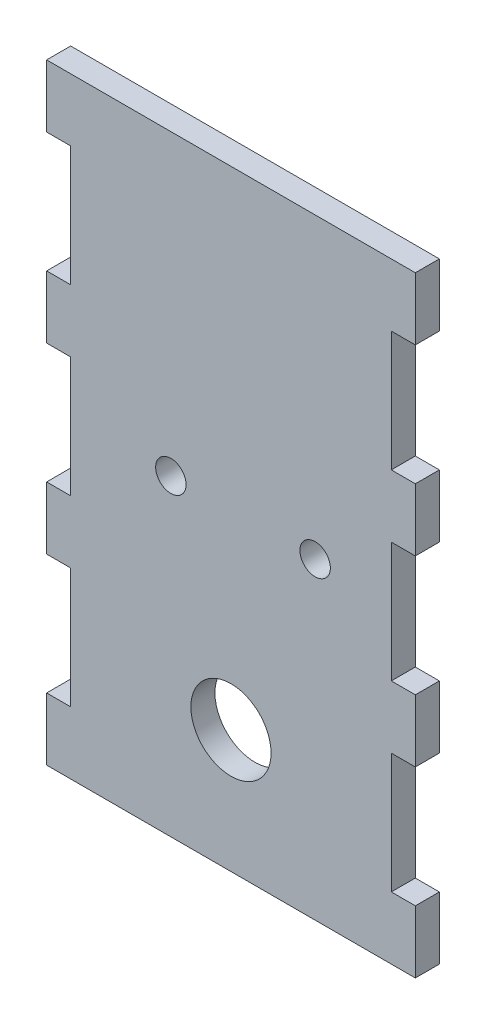
SolidWorks part; units mm, degrees
material "Oak"
ref_plane "Front Plane" through (0, 0, 0) normal (0, 0, 1) x (1, 0, 0)
ref_plane "Top Plane" through (0, 0, 0) normal (0, 1, 0) x (1, 0, 0)
ref_plane "Right Plane" through (0, 0, 0) normal (1, 0, 0) x (0, 0, -1)
sketch "Sketch1" plane through (0, 0, 0) normal (0, 0, 1) x (1, 0, 0)
  line L1 (-40.9935, 16.542) -> (5.0065, 16.542)
  line L2 (-40.9935, 16.542) -> (-40.9935, -59.658)
  line L3 (-40.9935, -59.658) -> (5.0065, -59.658)
  line L4 (5.0065, 16.542) -> (5.0065, -59.658)
  dimension "D1" = 76.2
  dimension "D2" = 46
extrude "Boss-Extrude1" add sketch "Sketch1" along normal blind 3
sketch "Sketch2" plane through (0, 0, 3) normal (0, 0, 1) x (1, 0, 0)
  line L0 (-40.9935, 16.542) -> (-40.9935, -59.658) construction
  line L1 (-40.9935, 8.742) -> (-37.9935, 8.742)
  line L2 (-40.9935, 8.742) -> (-40.9935, -6.258)
  line L3 (-40.9935, -6.258) -> (-37.9935, -6.258)
  line L4 (-37.9935, 8.742) -> (-37.9935, -6.258)
  line L5 (5.0065, 16.542) -> (-40.9935, 16.542) construction
  line L6 (5.0065, -59.658) -> (5.0065, 16.542) construction
  line L7 (5.0065, 8.742) -> (2.0065, 8.742)
  line L8 (5.0065, 8.742) -> (5.0065, -6.258)
  line L9 (5.0065, -6.258) -> (2.0065, -6.258)
  line L10 (2.0065, 8.742) -> (2.0065, -6.258)
  point P8 (-39.4935, 8.742)
  dimension "D1" = 3
  dimension "D2" = 7.8
  dimension "D3" = 15
  dimension "D4" = 3
  dimension "D5" = 7.8
  dimension "D6" = 15
extrude "Cut-Extrude1" cut sketch "Sketch2" against normal through all
pattern_linear "LPattern1" count 3 spacing 22.8 along (0, -1, 0) of "Cut-Extrude1"
hole_wizard "#6 Clearance Hole1" positions "Sketch3" profile "Sketch4" hole size "#6" standard "ANSI Inch" end condition through all
sketch "Sketch3" plane through (0, 0, 3) normal (0, 0, 1) x (1, 0, 0)
  point P0 (-25.4935, -20.658)
  point P3 (-7.4935, -20.658)
sketch "Sketch4" plane through (-25.4935, -20.658, 3) normal (1, 0, 0) x (0, -1, 0)
  line L0 (0, 0) -> (0, 3)
  line L1 (0, 3) -> (1.8986, 3)
  line L2 (1.8986, 3) -> (1.8986, 0)
  line L5 (1.8986, 0) -> (0, 0)
  line L11 (0, -6.35) -> (0, 107.95) construction
  dimension "Thru Hole Dia." = 3.7973
  dimension "Thru Hole Depth" = 3
sketch "Sketch5" plane through (0, 0, 0) normal (0, 0, -1) x (-1, 0, 0)
  line L0 (40.9935, -59.658) -> (-5.0065, -59.658) construction
  line L1 (-2.0065, -36.858) -> (-2.0065, -51.858) construction
  circle A0 centre (17.9935, -44.358) radius 5
  point P2 (0, 0)
  point P5 (17.9935, -59.658)
  point P8 (-2.0065, -44.358)
  dimension "D1" = 10
extrude "Cut-Extrude2" cut sketch "Sketch5" against normal up to next
